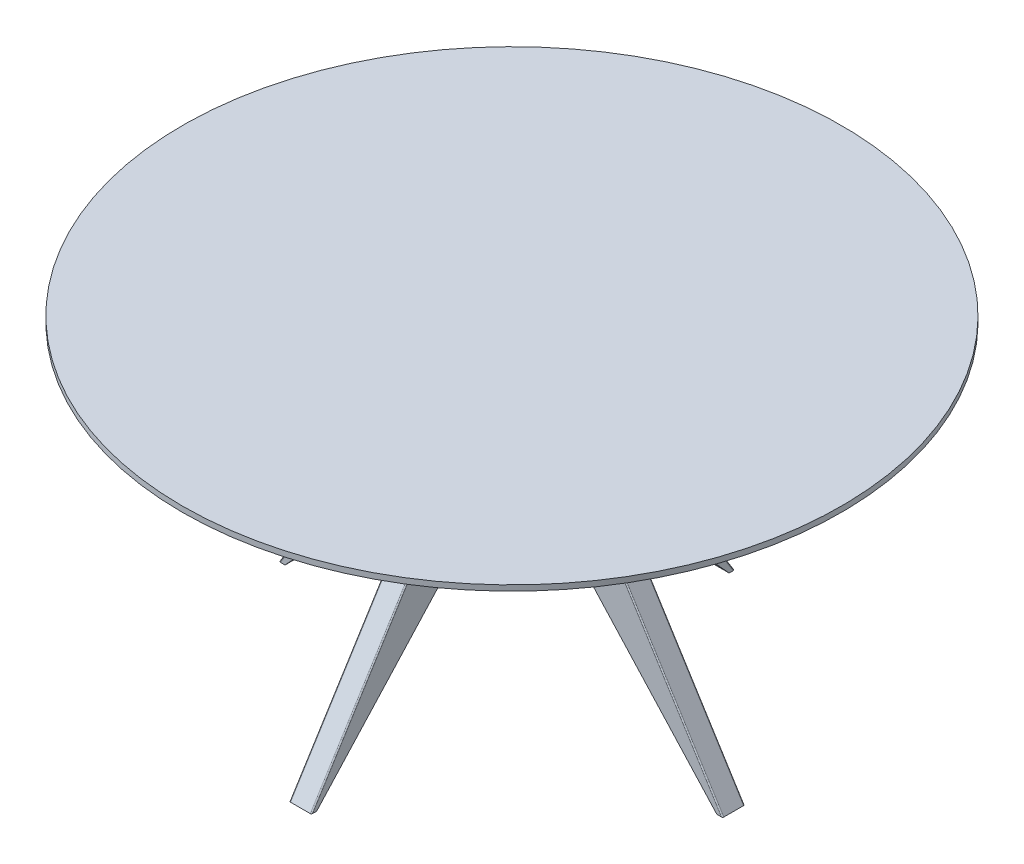
SolidWorks part; units mm, degrees
ref_plane "Front Plane" through (0, 0, 0) normal (0, 0, 1) x (1, 0, 0)
ref_plane "Top Plane" through (0, 0, 0) normal (0, 1, 0) x (1, 0, 0)
ref_plane "Right Plane" through (0, 0, 0) normal (1, 0, 0) x (0, 0, -1)
sketch "Sketch2" plane through (0, 0, 0) normal (0, 1, 0) x (1, 0, 0)
  circle A0 centre (0, 0) radius 762
extrude "Boss-Extrude1" add sketch "Sketch2" along normal blind 12.7
sketch "Sketch3" plane through (0, 0, 0) normal (1, 0, 0) x (0, 0, -1)
  line L0 (-519.6866, 0) -> (-222.872, -142.7161)
  line L1 (-762, 0) -> (762, 0) construction
  line L2 (-191.2759, -251.778) -> (-489.062, -728.2032)
  line L3 (-489.062, -728.2032) -> (-476.8513, -728.2032)
  line L4 (-476.8513, -728.2032) -> (0, -205.2924)
  line L5 (-376.5129, 0) -> (0, -97.7172)
  line L6 (-519.6866, 0) -> (-376.5129, 0)
  line L7 (0, -97.7172) -> (0, -205.2924)
  line L8 (0, 77.0647) -> (0, -285.9023) construction
  line L9 (376.5129, 0) -> (0, -97.7172)
  line L10 (519.6866, 0) -> (376.5129, 0)
  line L11 (519.6866, 0) -> (222.872, -142.7161)
  line L12 (191.2759, -251.778) -> (489.062, -728.2032)
  line L13 (489.062, -728.2032) -> (476.8513, -728.2032)
  line L14 (476.8513, -728.2032) -> (0, -205.2924)
  arc A0 (-222.872, -142.7161) -> (-191.2759, -251.778) centre (-255.8922, -211.3901) cw
  arc A1 (222.872, -142.7161) -> (191.2759, -251.778) centre (255.8922, -211.3901) ccw
  point P26 (0, -272.9005)
  point P27 (0, -43.202)
  dimension "D1" = 76.2
extrude "Boss-Extrude2" add sketch "Sketch3" along normal mid plane 50.8
sketch "Sketch5" plane through (0, 0, 0) normal (0, 0, 1) x (1, 0, 0)
  line L0 (-547.0368, 0.4054) -> (-249.591, -142.6143)
  line L1 (-217.995, -251.6761) -> (-512.75, -723.2519)
  line L2 (-512.75, -723.2519) -> (-499.1482, -723.2519)
  line L3 (-499.1482, -723.2519) -> (-3.1472, -179.3418)
  line L4 (-404.4013, 0.4054) -> (-3.1472, -103.733)
  line L5 (-547.0368, 0.4054) -> (-404.4013, 0.4054)
  line L6 (-3.1472, -103.733) -> (-3.1472, -179.3418)
  line L7 (0, 0) -> (0, -272.1956)
  line L8 (547.0368, 0.4054) -> (404.4013, 0.4054)
  line L9 (404.4013, 0.4054) -> (3.1472, -103.733)
  line L10 (3.1472, -103.733) -> (3.1472, -179.3418)
  line L11 (499.1482, -723.2519) -> (3.1472, -179.3418)
  line L12 (512.75, -723.2519) -> (499.1482, -723.2519)
  line L13 (217.995, -251.6761) -> (512.75, -723.2519)
  line L14 (547.0368, 0.4054) -> (249.591, -142.6143)
  arc A0 (-249.591, -142.6143) -> (-217.995, -251.6761) centre (-282.6112, -211.2882) cw
  arc A1 (249.591, -142.6143) -> (217.995, -251.6761) centre (282.6112, -211.2882) ccw
extrude "Boss-Extrude3" add sketch "Sketch5" along normal mid plane 50.8 contours L0 A0 L1 L2 L3 L6 L4 L5 | A1 L14 L8 L9 L10 L11 L12 L13
fillet "Fillet1" radius 50.8 1 edges at (25.4, -150.8508, 25.4)
fillet "Fillet2" radius 50.8 3 edges at (-25.4, -150.8508, 25.4) (-25.4, -150.8508, -25.4) (25.4, -150.8508, -25.4)
fillet "Fillet3" radius 2.54 24 edges at (-25.4, -71.3581, 371.2793) (25.4, -71.3581, 371.2793) (-25.4, -190.1862, 182.7017) (25.4, -190.1862, 182.7017) (-397.8924, -71.3071, -25.4) (-209.4208, -190.0843, -25.4) (-397.8924, -71.3071, 25.4) (-209.4208, -190.0843, 25.4) (-25.4, -489.9906, 340.1689) (25.4, -489.9906, 340.1689) (-365.3725, -487.464, -25.4) (-365.3725, -487.464, 25.4) (-25.4, -71.3581, -371.2793) (25.4, -71.3581, -371.2793) (-25.4, -190.1862, -182.7017) (25.4, -190.1862, -182.7017) (397.8924, -71.3071, -25.4) (209.4208, -190.0843, -25.4) (397.8924, -71.3071, 25.4) (209.4208, -190.0843, 25.4) (-25.4, -489.9906, -340.1689) (25.4, -489.9906, -340.1689) (365.3725, -487.464, -25.4) (365.3725, -487.464, 25.4)
